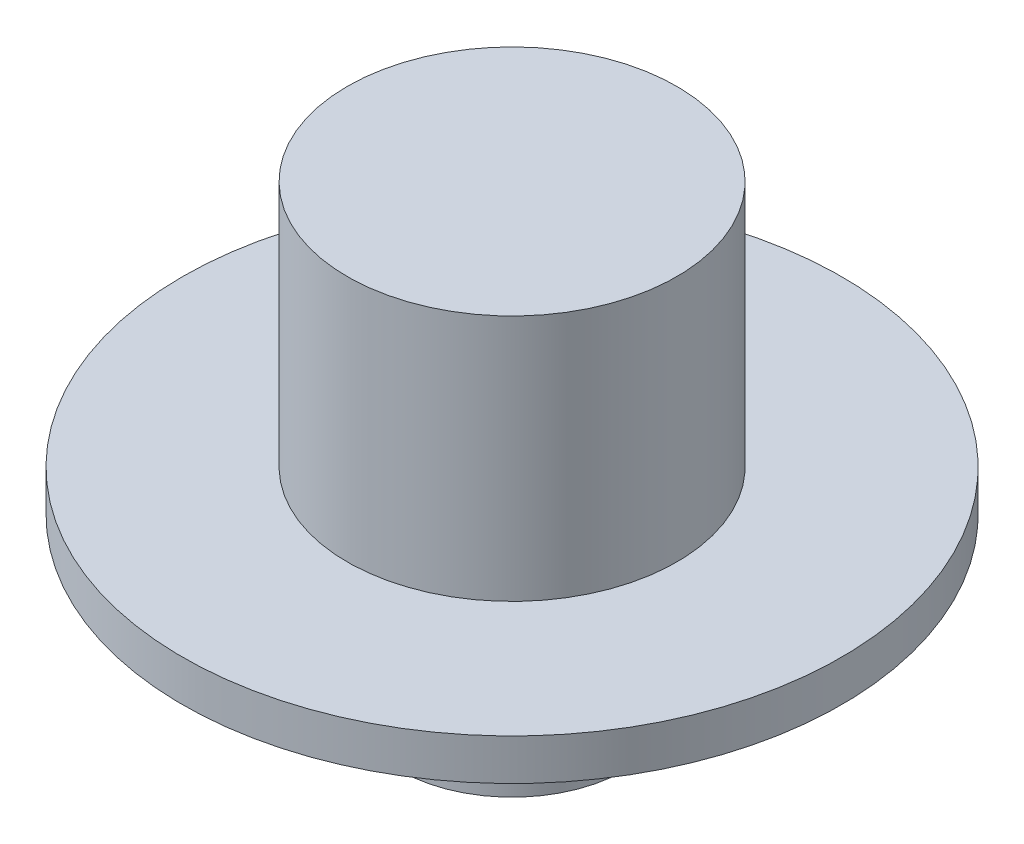
SolidWorks part; units mm, degrees
ref_plane "Front Plane" through (0, 0, 0) normal (0, 0, 1) x (1, 0, 0)
ref_plane "Top Plane" through (0, 0, 0) normal (0, 1, 0) x (1, 0, 0)
ref_plane "Right Plane" through (0, 0, 0) normal (1, 0, 0) x (0, 0, -1)
sketch "Sketch1" plane through (0, 0, 0) normal (0, 0, 1) x (1, 0, 0)
  line L0 (0, 0) -> (1.375, 0)
  line L1 (1.375, 0) -> (1.375, 2)
  line L2 (1.375, 2) -> (4, 2)
  line L3 (4, 2) -> (4, 2.5)
  line L4 (4, 2.5) -> (2, 2.5)
  line L5 (2, 2.5) -> (2, 5.5)
  line L6 (2, 5.5) -> (0, 5.5)
  line L7 (0, 5.5) -> (0, 0) construction
  line L8 (0, 0) -> (0, 5.5)
  dimension "D1" = 1.375
  dimension "D2" = 2
  dimension "D3" = 0.5
  dimension "D4" = 3
  dimension "D5" = 2
  dimension "D6" = 2
revolve "Revolve1" add sketch "Sketch1" angle 360 about L7
